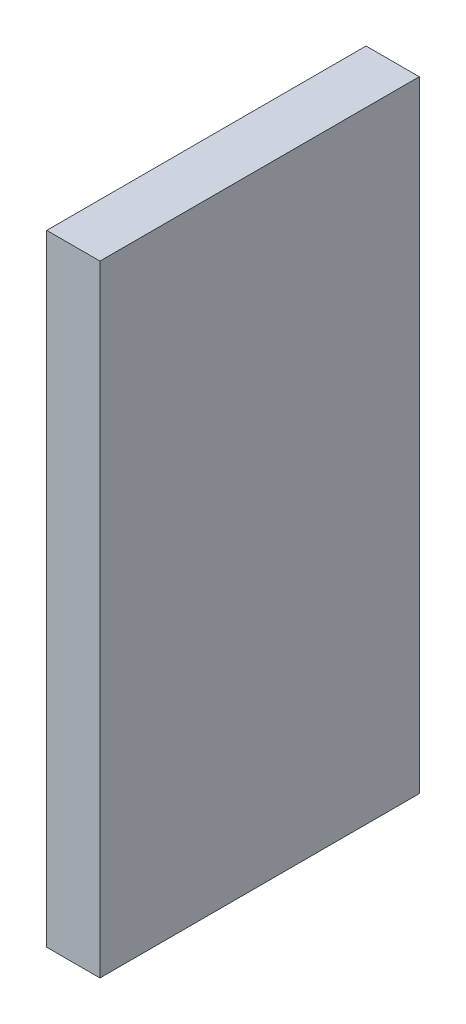
SolidWorks part; units mm, degrees
material "Silicon Rubber"
ref_plane "Front Plane" through (0, 0, 0) normal (0, 0, 1) x (1, 0, 0)
ref_plane "Top Plane" through (0, 0, 0) normal (0, 1, 0) x (1, 0, 0)
ref_plane "Right Plane" through (0, 0, 0) normal (1, 0, 0) x (0, 0, -1)
sketch "Sketch1" plane through (0, 0, 0) normal (1, 0, 0) x (0, 0, -1)
  line L0 (-9, -17.5) -> (-9, 17.5)
  line L1 (-9, 17.5) -> (9, 17.5)
  line L2 (9, 17.5) -> (9, -17.5)
  line L3 (9, -17.5) -> (-9, -17.5)
extrude "Boss-Extrude1" add sketch "Sketch1" along normal blind 3
